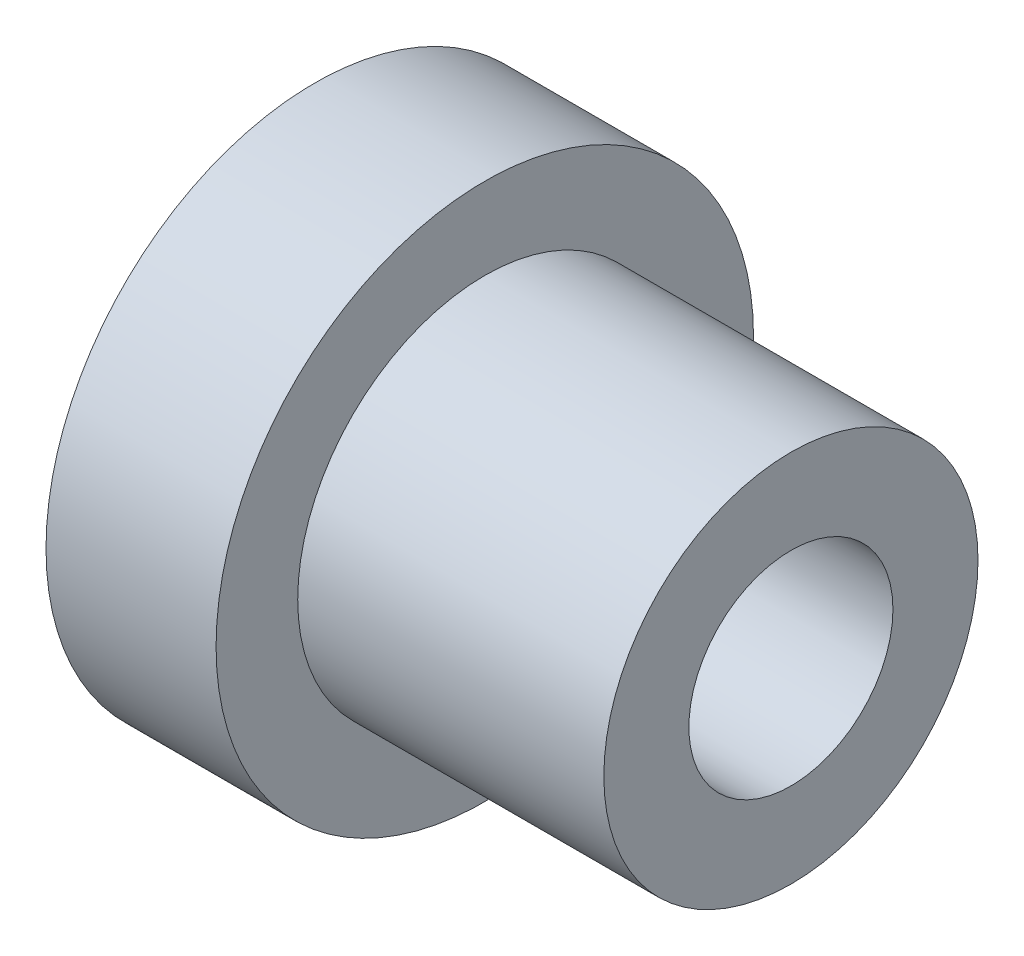
SolidWorks part; units mm, degrees
material "6061 Alloy"
ref_plane "Front Plane" through (0, 0, 0) normal (0, 0, 1) x (1, 0, 0)
ref_plane "Top Plane" through (0, 0, 0) normal (0, 1, 0) x (1, 0, 0)
ref_plane "Right Plane" through (0, 0, 0) normal (1, 0, 0) x (0, 0, -1)
sketch "Sketch1" plane through (0, 0, 0) normal (0, 0, 1) x (1, 0, 0)
  line L0 (-2.85, 5.6) -> (-2.85, 8)
  line L1 (-2.85, 8) -> (-7.85, 8)
  line L2 (-7.85, 8) -> (-7.85, 6)
  line L3 (-7.85, 6) -> (-5.35, 6)
  line L4 (-5.35, 6) -> (-5.35, 3.1)
  line L5 (-5.35, 3.1) -> (6.15, 3.1)
  line L6 (6.15, 3.1) -> (6.15, 5.6)
  line L7 (6.15, 5.6) -> (-2.85, 5.6)
  line L8 (-7.85, 0.1) -> (6.15, 0.1) construction
  dimension "D1" = 5.5
  dimension "D2" = 3
revolve "Revolve1" add sketch "Sketch1" angle 360 about L8
